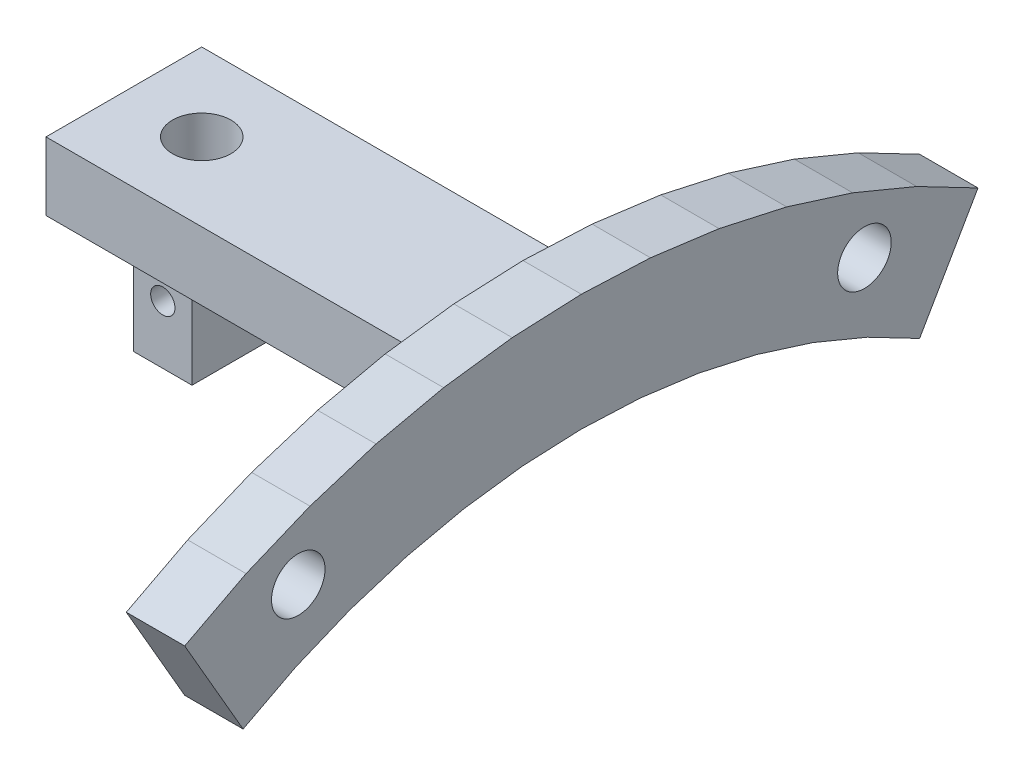
SolidWorks part; units mm, degrees
ref_plane "Front Plane" through (0, 0, 0) normal (0, 0, 1) x (1, 0, 0)
ref_plane "Top Plane" through (0, 0, 0) normal (0, 1, 0) x (1, 0, 0)
ref_plane "Right Plane" through (0, 0, 0) normal (1, 0, 0) x (0, 0, -1)
ref_plane "Foot Plane" through (-9, 0, 0) normal (1, 0, 0) x (0, 0, -1)
sketch "Foot Sketch" plane through (-9, 0, 0) normal (1, 0, 0) x (0, 0, -1)
  line L0 (-40.75, 70.5811) -> (-34.4434, 73.8641)
  line L1 (-34.4434, 73.8641) -> (-27.8746, 76.5849)
  line L2 (-27.8746, 76.5849) -> (-21.0938, 78.723)
  line L3 (-21.0938, 78.723) -> (-14.1523, 80.2618)
  line L4 (-14.1523, 80.2618) -> (-7.1032, 81.1899)
  line L5 (-7.1032, 81.1899) -> (0, 81.5)
  line L6 (0, 81.5) -> (7.1032, 81.1899)
  line L7 (7.1032, 81.1899) -> (14.1523, 80.2618)
  line L8 (14.1523, 80.2618) -> (21.0938, 78.723)
  line L9 (21.0938, 78.723) -> (27.8746, 76.5849)
  line L10 (27.8746, 76.5849) -> (34.4434, 73.8641)
  line L11 (34.4434, 73.8641) -> (40.75, 70.5811)
  line L12 (40.75, 70.5811) -> (34.75, 60.1888)
  line L13 (34.75, 60.1888) -> (29.372, 62.9884)
  line L14 (29.372, 62.9884) -> (23.7704, 65.3086)
  line L15 (23.7704, 65.3086) -> (17.9879, 67.1318)
  line L16 (17.9879, 67.1318) -> (12.0685, 68.4441)
  line L17 (12.0685, 68.4441) -> (6.0573, 69.2355)
  line L18 (6.0573, 69.2355) -> (0, 69.5)
  line L19 (0, 69.5) -> (-6.0573, 69.2355)
  line L20 (-6.0573, 69.2355) -> (-12.0685, 68.4441)
  line L21 (-12.0685, 68.4441) -> (-17.9879, 67.1318)
  line L22 (-17.9879, 67.1318) -> (-23.7704, 65.3086)
  line L23 (-23.7704, 65.3086) -> (-29.372, 62.9884)
  line L24 (-29.372, 62.9884) -> (-34.75, 60.1888)
  line L25 (-34.75, 60.1888) -> (-40.75, 70.5811)
extrude "Foot" add sketch "Foot Sketch" against normal blind 6
sketch "Riser Sketch" plane through (0, 0, 0) normal (0, 0, 1) x (1, 0, 0)
  line L0 (-56, 69) -> (-15, 69)
  line L1 (-15, 69) -> (-15, 76)
  line L2 (-15, 76) -> (-56, 76)
  line L3 (-56, 76) -> (-56, 69)
extrude "Riser" add sketch "Riser Sketch" along normal mid plane 16
sketch "Tab Sketch" plane through (0, 0, 0) normal (0, 0, 1) x (1, 0, 0)
  line L0 (-51, 57.4) -> (-45, 57.4)
  line L1 (-45, 57.4) -> (-45, 69)
  line L2 (-45, 69) -> (-51, 69)
  line L3 (-51, 69) -> (-51, 57.4)
extrude "Pushrod Tab" add sketch "Tab Sketch" along normal mid plane 8
sketch "Pin Hole Sketch" plane through (0, 0, 0) normal (0, 0, 1) x (1, 0, 0)
  line L0 (-48, 59) -> (-48, 86) construction
  line L1 (-48, 70) -> (-45, 70)
  line L2 (-45, 70) -> (-45, 77)
  line L3 (-45, 77) -> (-48, 77)
  line L4 (-48, 77) -> (-48, 70)
revolve "Pin Hole" cut sketch "Pin Hole Sketch" angle 360 about L0
sketch "Ball Joint Hole Sketch" plane through (0, 0, 0) normal (0, 0, 1) x (1, 0, 0)
  circle A0 centre (-48, 63.4) radius 1.25
extrude "Ball Joint Hole" cut sketch "Ball Joint Hole Sketch" against normal mid plane 10
sketch "Foot Bolt Hole +22.5 Sketch" plane through (-9, 0, 0) normal (1, 0, 0) x (0, 0, -1)
  circle A0 centre (29.0839, 70.2148) radius 2.75
extrude "Foot Bolt Hole +22.5" cut sketch "Foot Bolt Hole +22.5 Sketch" against normal blind 6
sketch "Foot Bolt Hole -22.5 Sketch" plane through (-9, 0, 0) normal (1, 0, 0) x (0, 0, -1)
  circle A0 centre (-29.0839, 70.2148) radius 2.75
extrude "Foot Bolt Hole -22.5" cut sketch "Foot Bolt Hole -22.5 Sketch" against normal blind 6
